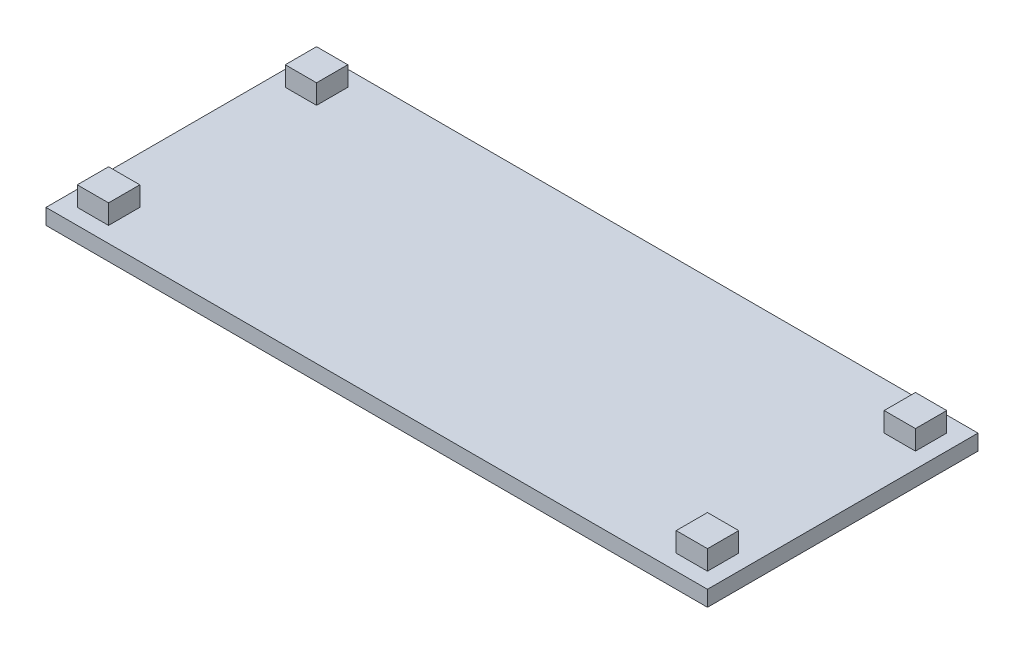
SolidWorks part; units mm, degrees
ref_plane "前视基准面" through (0, 0, 0) normal (0, 0, 1) x (1, 0, 0)
ref_plane "上视基准面" through (0, 0, 0) normal (0, 1, 0) x (1, 0, 0)
ref_plane "右视基准面" through (0, 0, 0) normal (1, 0, 0) x (0, 0, -1)
other "Configuration Table"
sketch "草图1" plane through (0, 0, 0) normal (0, 1, 0) x (1, 0, 0)
  line L1 (-42.3, -17.3) -> (42.3, -17.3)
  line L2 (-42.3, -17.3) -> (-42.3, 17.3)
  line L3 (-42.3, 17.3) -> (42.3, 17.3)
  line L4 (42.3, -17.3) -> (42.3, 17.3)
  line L5 (-42.3, -17.3) -> (42.3, 17.3) construction
  line L6 (-42.3, 17.3) -> (42.3, -17.3) construction
extrude "凸台-拉伸1" add sketch "草图1" along normal blind 2
sketch "草图2" plane through (0, 0, 0) normal (0, 1, 0) x (1, 0, 0)
  line L0 (-42.3, -17.3) -> (42.3, -17.3) construction
  line L1 (40.3, -17.3) -> (42.3, -17.3)
  line L2 (40.3, -17.3) -> (40.3, 17.3)
  line L3 (40.3, 17.3) -> (42.3, 17.3)
  line L4 (42.3, -17.3) -> (42.3, 17.3)
  line L5 (-42.3, 17.3) -> (-42.3, -17.3) construction
  line L6 (-42.3, 15.3) -> (42.3, 15.3)
  line L7 (-42.3, 15.3) -> (-42.3, 17.3)
  line L8 (-42.3, 17.3) -> (42.3, 17.3)
  line L9 (42.3, 15.3) -> (42.3, 17.3)
  line L11 (-42.3, -17.3) -> (42.3, -17.3)
  line L12 (-42.3, -17.3) -> (-42.3, -15.3)
  line L13 (-42.3, -15.3) -> (42.3, -15.3)
  line L14 (42.3, -17.3) -> (42.3, -15.3)
  line L15 (-42.3, 7) -> (-40.3, 7)
  line L16 (-42.3, 7) -> (-42.3, 17.3)
  line L17 (-42.3, 17.3) -> (-40.3, 17.3)
  line L18 (-40.3, 7) -> (-40.3, 17.3)
  line L19 (-42.3, -17.3) -> (-40.3, -17.3)
  line L20 (-42.3, -17.3) -> (-42.3, -7)
  line L21 (-42.3, -7) -> (-40.3, -7)
  line L22 (-40.3, -17.3) -> (-40.3, -7)
sketch "草图3" plane through (0, 0, 0) normal (0, 1, 0) x (1, 0, 0)
  line L0 (40.3, -17.3) -> (40.3, 17.3) construction
  line L1 (36.3, 11.3) -> (40.3, 11.3)
  line L2 (36.3, 11.3) -> (36.3, 15.3)
  line L3 (36.3, 15.3) -> (40.3, 15.3)
  line L4 (40.3, 11.3) -> (40.3, 15.3)
  line L5 (-42.3, 15.3) -> (42.3, 15.3) construction
  line L6 (36.3, -11.3) -> (40.3, -11.3)
  line L7 (36.3, -11.3) -> (36.3, -15.3)
  line L8 (36.3, -15.3) -> (40.3, -15.3)
  line L9 (40.3, -11.3) -> (40.3, -15.3)
  line L10 (-36.3, 11.3) -> (-40.3, 11.3)
  line L11 (-36.3, 11.3) -> (-36.3, 15.3)
  line L12 (-36.3, 15.3) -> (-40.3, 15.3)
  line L13 (-40.3, 11.3) -> (-40.3, 15.3)
  line L14 (-42.3, -15.3) -> (42.3, -15.3) construction
  line L15 (-36.3, -11.3) -> (-40.3, -11.3)
  line L16 (-36.3, -11.3) -> (-36.3, -15.3)
  line L17 (-36.3, -15.3) -> (-40.3, -15.3)
  line L18 (-40.3, -11.3) -> (-40.3, -15.3)
extrude "凸台-拉伸3" add sketch "草图3" along normal blind 4.5
